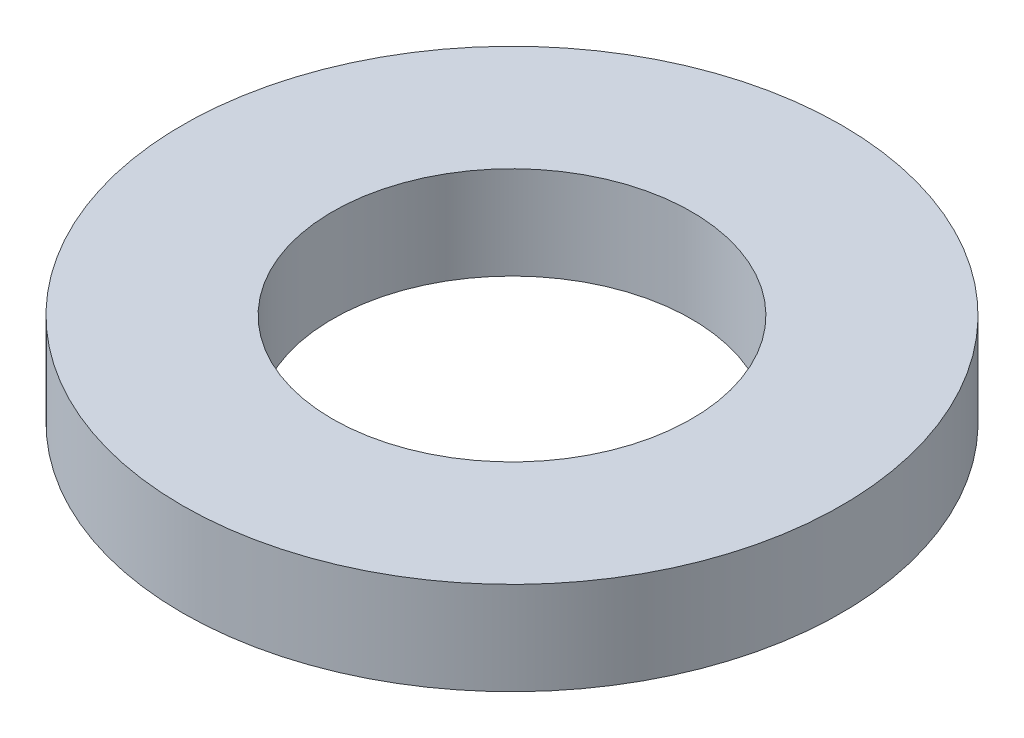
SolidWorks part; units mm, degrees
material "AISI 304"
ref_plane "Front Plane" through (0, 0, 0) normal (0, 0, 1) x (1, 0, 0)
ref_plane "Top Plane" through (0, 0, 0) normal (0, 1, 0) x (1, 0, 0)
ref_plane "Right Plane" through (0, 0, 0) normal (1, 0, 0) x (0, 0, -1)
sketch "Sketch1" plane through (0, 0, 0) normal (0, 1, 0) x (1, 0, 0)
  circle A0 centre (0, 0) radius 5.9436
  dimension "OD" = 11.8872
extrude "Boss-Extrude1" add sketch "Sketch1" along normal blind 1.6764
sketch "Sketch5" plane through (0, 1.6764, 0) normal (0, 1, 0) x (-1, 0, 0)
  circle A0 centre (0, 0) radius 3.2385
  dimension "ID" = 6.477
extrude "Cut-Extrude1" cut sketch "Sketch5" against normal through all
